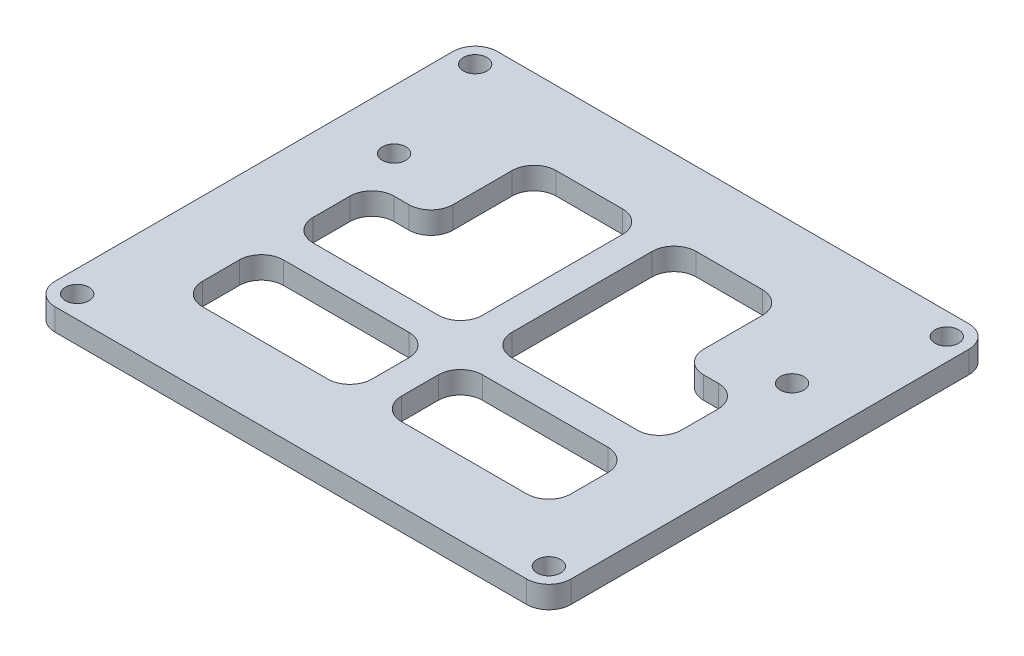
SolidWorks part; units mm, degrees
ref_plane "前视基准面" through (0, 0, 0) normal (0, 0, 1) x (1, 0, 0)
ref_plane "上视基准面" through (0, 0, 0) normal (0, 1, 0) x (1, 0, 0)
ref_plane "右视基准面" through (0, 0, 0) normal (1, 0, 0) x (0, 0, -1)
other "Configuration Table"
sketch "草图1" plane through (0, 0, 0) normal (0, 1, 0) x (1, 0, 0)
  line L1 (-32, 30) -> (32, 30)
  line L2 (-35, 27) -> (-35, -27)
  line L3 (-32, -30) -> (32, -30)
  line L4 (35, 27) -> (35, -27)
  line L5 (-35, 30) -> (35, -30) construction
  line L6 (-35, -30) -> (35, 30) construction
  line L7 (-32, 27) -> (32, 27) construction
  line L8 (-32, 27) -> (-32, -27) construction
  line L9 (-32, -27) -> (32, -27) construction
  line L10 (32, 27) -> (32, -27) construction
  line L11 (-32, 27) -> (32, -27) construction
  line L12 (-32, -27) -> (32, 27) construction
  circle A0 centre (-32, 27) radius 1.6
  circle A1 centre (32, 27) radius 1.6
  circle A2 centre (-32, -27) radius 1.6
  circle A3 centre (32, -27) radius 1.6
  arc A4 (32, -30) -> (35, -27) centre (32, -27) ccw
  arc A5 (-32, -30) -> (-35, -27) centre (-32, -27) cw
  arc A6 (35, 27) -> (32, 30) centre (32, 27) ccw
  arc A7 (-35, 27) -> (-32, 30) centre (-32, 27) cw
  point P0 (0, 0)
  point P6 (0, 0)
  point P13 (-31.5, 27)
  point P15 (32.1035, 27)
  point P17 (-32.1951, -27)
  point P19 (32.2345, -27)
  dimension "D5" = 3.2
  dimension "D6" = 3.2
  dimension "D7" = 3.2
  dimension "D8" = 3.2
  dimension "D9" = 3
  dimension "D1" = 60
  dimension "D2" = 70
  dimension "D3" = 64
  dimension "D4" = 54
extrude "凸台-拉伸1" add sketch "草图1" along normal blind 3
sketch "草图2" plane through (0, 3, 0) normal (0, 1, 0) x (1, 0, 0)
  line L0 (0, 43.6159) -> (0, -46.3448) construction
  circle A0 centre (-27, 11) radius 1.6
  circle A1 centre (27, 11) radius 1.6
  circle A2 centre (-32, 27) radius 1.6 construction
  circle A3 centre (-32, 27) radius 1.6
  dimension "D1" = 3.2
  dimension "D2" = 16
  dimension "D3" = 54
extrude "切除-拉伸1" cut sketch "草图2" against normal blind 3
sketch "草图3" plane through (0, 0, 0) normal (0, -1, 0) x (1, 0, 0)
  line L0 (35, 27) -> (35, -27) construction
  line L1 (-22, 20) -> (-5, 20)
  line L2 (-25, 17) -> (-25, 12)
  line L3 (-22, -6) -> (-20, -6)
  line L4 (25, 17) -> (25, 12)
  line L5 (-25, 20) -> (25, -6) construction
  line L6 (-25, -6) -> (25, 20) construction
  line L7 (-35, -27) -> (-35, 27) construction
  line L8 (-32, 30) -> (32, 30) construction
  line L9 (32, -30) -> (-32, -30) construction
  line L12 (-14, -20) -> (-5, -20)
  line L13 (17, -9) -> (17, -17)
  line L14 (-6.0381, -6) -> (17, -20) construction
  line L15 (-17, -20) -> (6.0381, -6) construction
  line L16 (-25, 7) -> (25, 7) construction
  line L17 (-22, 9) -> (-5, 9)
  line L18 (-22, 5) -> (-5, 5)
  line L19 (0, 20) -> (0, -20.4465) construction
  line L20 (-2, 17) -> (-2, 12)
  line L21 (2, 17) -> (2, 12)
  line L22 (-17, -9) -> (-17, -17)
  line L23 (20, -6) -> (22, -6)
  line L24 (5, 5) -> (22, 5)
  line L25 (-2, 2) -> (-2, -17)
  line L26 (4.9993, -19.9978) -> (14, -20)
  line L27 (5, 9) -> (22, 9)
  line L28 (2, 2) -> (2, -16.9978)
  line L29 (-25, 2) -> (-25, -3)
  line L30 (5, 20) -> (22, 20)
  line L31 (25, 2) -> (25, -3)
  circle A0 centre (-27, -11) radius 1.6 construction
  circle A1 centre (27, -11) radius 1.6 construction
  arc A2 (17, -9) -> (20, -6) centre (20, -9) cw
  arc A3 (22, -6) -> (25, -3) centre (22, -3) ccw
  arc A4 (25, 17) -> (22, 20) centre (22, 17) ccw
  arc A5 (-22, -6) -> (-25, -3) centre (-22, -3) cw
  arc A6 (-25, 17) -> (-22, 20) centre (-22, 17) cw
  arc A7 (-17, -9) -> (-20, -6) centre (-20, -9) ccw
  arc A8 (-14, -20) -> (-17, -17) centre (-14, -17) cw
  arc A9 (14, -20) -> (17, -17) centre (14, -17) ccw
  arc A10 (-5, -20) -> (-2, -17) centre (-5, -17) ccw
  arc A11 (-2, 2) -> (-5, 5) centre (-5, 2) ccw
  arc A12 (2, 2) -> (5, 5) centre (5, 2) cw
  arc A13 (5, 9) -> (2, 12) centre (5, 12) cw
  arc A14 (-5, 9) -> (-2, 12) centre (-5, 12) ccw
  arc A15 (4.9993, -19.9978) -> (2, -16.9978) centre (5, -16.9978) cw
  arc A16 (25, 12) -> (22, 9) centre (22, 12) cw
  arc A17 (25, 2) -> (22, 5) centre (22, 2) ccw
  arc A18 (2, 17) -> (5, 20) centre (5, 17) cw
  arc A19 (-2, 17) -> (-5, 20) centre (-5, 17) ccw
  arc A20 (-25, 2) -> (-22, 5) centre (-22, 2) cw
  arc A21 (-22, 9) -> (-25, 12) centre (-22, 12) cw
  point P0 (0, 7)
  point P13 (0, -9.6693)
  point P43 (17, -6)
  point P69 (-2, 5)
  point P81 (25, 9)
  point P84 (25, 5)
  point P87 (2, 20)
  point P90 (-2, 20)
  point P93 (-25, 5)
  point P96 (-25, 9)
  point P97 (14.0055, -20)
  dimension "D7" = 3
  dimension "D10" = 3
  dimension "D11" = 3
  dimension "D12" = 3
  dimension "D13" = 3
  dimension "D1" = 10
  dimension "D2" = 10
  dimension "D3" = 10
  dimension "D4" = 5
  dimension "D5" = 10
  dimension "D6" = 10
  dimension "D8" = 4
  dimension "D9" = 4
extrude "切除-拉伸2" cut sketch "草图3" against normal blind 3
